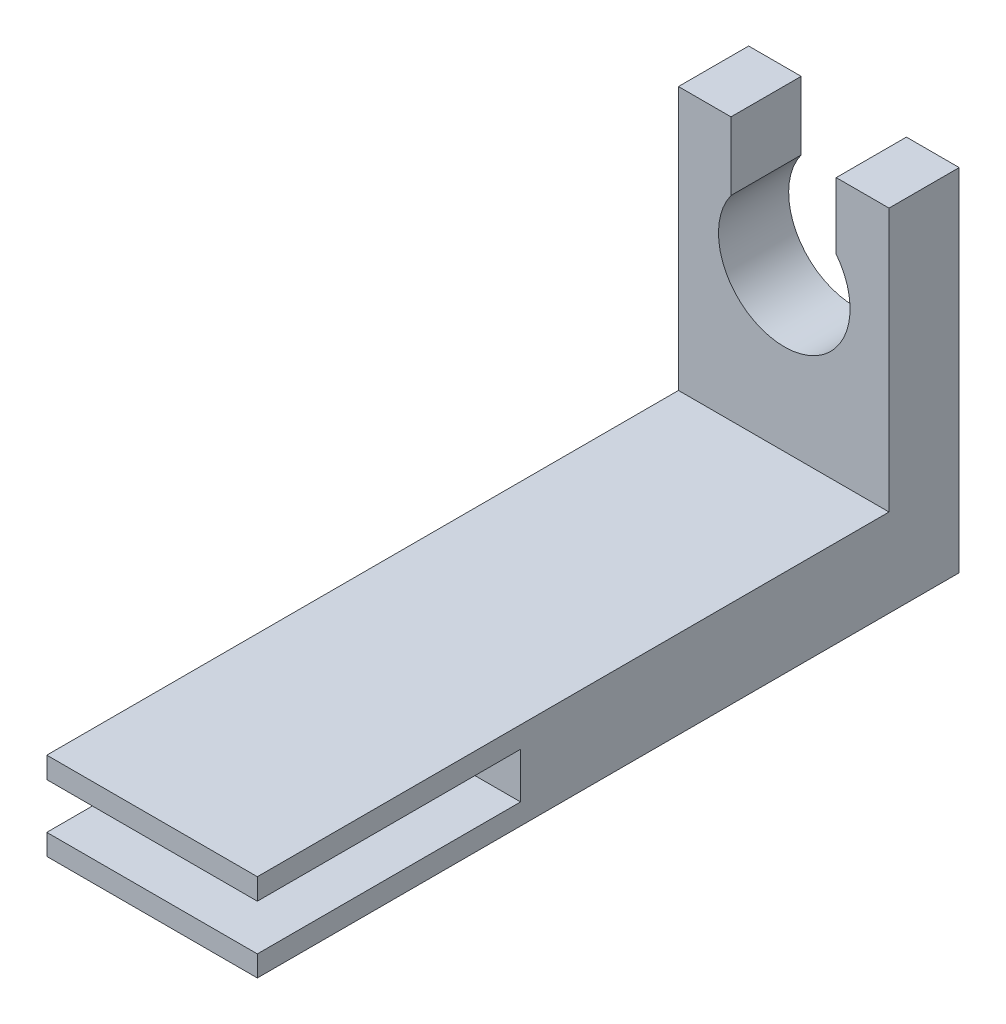
SolidWorks part; units mm, degrees
ref_plane "Front Plane" through (0, 0, 0) normal (0, 0, 1) x (1, 0, 0)
ref_plane "Top Plane" through (0, 0, 0) normal (0, 1, 0) x (1, 0, 0)
ref_plane "Right Plane" through (0, 0, 0) normal (1, 0, 0) x (0, 0, -1)
sketch "Sketch2" plane through (0, 0, 0) normal (0, 1, 0) x (1, 0, 0)
  line L1 (-15.7647, 43.0588) -> (-3.7647, 43.0588)
  line L2 (-15.7647, 43.0588) -> (-15.7647, 3.0588)
  line L3 (-15.7647, 3.0588) -> (-3.7647, 3.0588)
  line L4 (-3.7647, 43.0588) -> (-3.7647, 3.0588)
  line L5 (-15.7647, 43.0588) -> (-3.7647, 3.0588) construction
  line L6 (-15.7647, 3.0588) -> (-3.7647, 43.0588) construction
  point P0 (-9.7647, 23.0588)
  dimension "D1" = 40
  dimension "D2" = 12
extrude "Boss-Extrude1" add sketch "Sketch2" along normal blind 5
sketch "Sketch3" plane through (0, 0, -3.0588) normal (0, 0, 1) x (1, 0, 0)
  line L0 (-3.7647, 5) -> (-3.7647, 0) construction
  line L1 (-15.7688, 1.1896) -> (-3.7647, 1.1896)
  line L2 (-15.7688, 1.1896) -> (-15.7688, 3.7896)
  line L3 (-15.7688, 3.7896) -> (-3.7647, 3.7896)
  line L4 (-3.7647, 1.1896) -> (-3.7647, 3.7896)
  line L5 (-15.7688, 1.1896) -> (-3.7647, 3.7896) construction
  line L6 (-15.7688, 3.7896) -> (-3.7647, 1.1896) construction
  point P0 (-9.7668, 2.4896)
  dimension "D1" = 2.6
extrude "Cut-Extrude1" cut sketch "Sketch3" against normal blind 15
sketch "Sketch4" plane through (0, 5, 0) normal (0, 1, 0) x (1, 0, 0)
  line L0 (-3.7647, 3.0588) -> (-3.7647, 43.0588) construction
  line L1 (-15.7647, 43.0588) -> (-3.7647, 43.0588)
  line L2 (-15.7647, 43.0588) -> (-15.7647, 39.0588)
  line L3 (-15.7647, 39.0588) -> (-3.7647, 39.0588)
  line L4 (-3.7647, 43.0588) -> (-3.7647, 39.0588)
  dimension "D1" = 4
extrude "Boss-Extrude2" add sketch "Sketch4" along normal blind 15
sketch "Sketch5" plane through (0, 0, -43.0588) normal (0, 0, -1) x (-1, 0, 0)
  circle A0 centre (9.7348, 13.9179) radius 3.75
  dimension "D1" = 7.5
extrude "Cut-Extrude2" cut sketch "Sketch5" against normal blind 15
sketch "Sketch6" plane through (0, 0, -43.0588) normal (0, 0, -1) x (-1, 0, 0)
  line L0 (3.7647, 20) -> (15.7647, 20) construction
  line L1 (6.7739, 20) -> (12.7716, 20)
  line L2 (6.7739, 20) -> (6.7739, 16.118)
  line L3 (6.7739, 16.118) -> (12.7716, 16.118)
  line L4 (12.7716, 20) -> (12.7716, 16.118)
  circle A0 centre (9.7348, 13.9179) radius 3.75 construction
extrude "Cut-Extrude3" cut sketch "Sketch6" against normal blind 10
